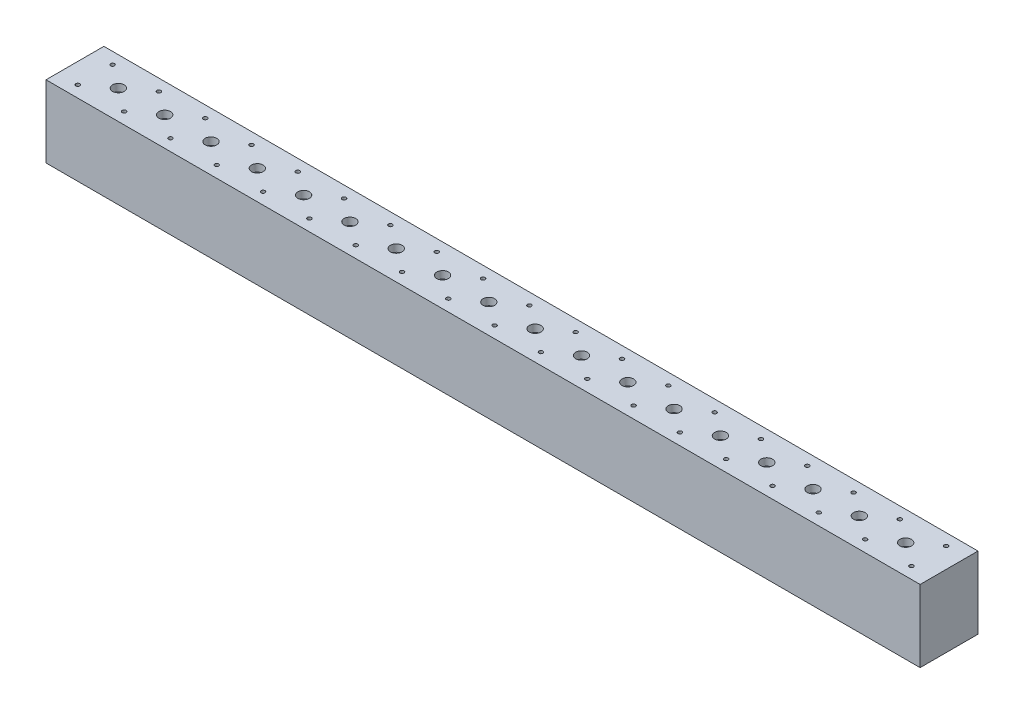
SolidWorks part; units mm, degrees
material "Plain Carbon Steel"
ref_plane "Front Plane" through (0, 0, 0) normal (0, 0, 1) x (1, 0, 0)
ref_plane "Top Plane" through (0, 0, 0) normal (0, 1, 0) x (1, 0, 0)
ref_plane "Right Plane" through (0, 0, 0) normal (1, 0, 0) x (0, 0, -1)
sketch "Sketch1" plane through (0, 0, 0) normal (0, 0, 1) x (1, 0, 0)
  line L0 (-755, 15) -> (755, 15)
  line L3 (755, 15) -> (755, 139.5)
  line L4 (0, 0) -> (0, 15) construction
  line L5 (-755, 15) -> (-755, 139.5)
  line L8 (-755, 139.5) -> (755, 139.5)
  line L9 (755, 15) -> (-755, 15) construction
  dimension "D1" = 124.5
  dimension "D4" = 1510
extrude "Boss-Extrude1" add sketch "Sketch1" against normal blind 100
ref_plane "Plane1" through (0, 0, -50) normal (0, 0, -1) x (-1, 0, 0)
hole_wizard "M8 Tapped Hole1" positions "Sketch4" profile "Sketch3" tap size "M8" standard "ISO"
sketch "Sketch4" plane through (0, 139.5, 0) normal (0, 1, 0) x (1, 0, 0)
  point P0 (720, 80)
  point P3 (720, 20)
  point P6 (640, 20)
  point P9 (640, 80)
  point P12 (560, 80)
  point P15 (560, 20)
  point P18 (480, 20)
  point P21 (480, 80)
  point P24 (400, 80)
  point P27 (400, 20)
  point P30 (320, 20)
  point P33 (320, 80)
  point P36 (240, 80)
  point P39 (240, 20)
  point P42 (160, 20)
  point P45 (160, 80)
  point P48 (80, 80)
  point P51 (80, 20)
  point P54 (0, 20)
  point P57 (0, 80)
  point P60 (-80, 80)
  point P63 (-80, 20)
  point P66 (-160, 20)
  point P69 (-160, 80)
  point P72 (-240, 80)
  point P75 (-240, 20)
  point P78 (-320, 20)
  point P81 (-320, 80)
  point P84 (-400, 80)
  point P87 (-400, 20)
  point P90 (-480, 20)
  point P93 (-480, 80)
  point P96 (-560, 20)
  point P99 (-560, 80)
  point P102 (-640, 20)
  point P105 (-640, 80)
  point P108 (-720, 80)
  point P111 (-720, 20)
sketch "Sketch3" plane through (720, 139.5, -80) normal (1, 0, 0) x (0, 0, 1)
  line L0 (0, 0) -> (0, 24.2929)
  line L1 (0, 24.2929) -> (3.4, 22.25)
  line L2 (3.4, 22.25) -> (3.4, 0)
  line L5 (3.4, 0) -> (0, 0)
  line L10 (0, 24.2929) -> (-3.4, 22.25) construction
  line L11 (0, -6.35) -> (0, 107.95) construction
  dimension "Tap Drill Dia." = 6.8
  dimension "Tap Drill Depth" = 22.25
  dimension "Drill Angle" = 118
cosmetic thread "Hole Thread1" parameters "D1"=16, "D2"=8
cosmetic thread "Hole Thread2" parameters "D1"=16, "D2"=8
cosmetic thread "Hole Thread3" parameters "D1"=16, "D2"=8
cosmetic thread "Hole Thread4" parameters "D1"=16, "D2"=8
cosmetic thread "Hole Thread5" parameters "D1"=16, "D2"=8
cosmetic thread "Hole Thread6" parameters "D1"=16, "D2"=8
cosmetic thread "Hole Thread7" parameters "D1"=16, "D2"=8
cosmetic thread "Hole Thread8" parameters "D1"=16, "D2"=8
cosmetic thread "Hole Thread9" parameters "D1"=16, "D2"=8
cosmetic thread "Hole Thread10" parameters "D1"=16, "D2"=8
cosmetic thread "Hole Thread11" parameters "D1"=16, "D2"=8
cosmetic thread "Hole Thread12" parameters "D1"=16, "D2"=8
cosmetic thread "Hole Thread13" parameters "D1"=16, "D2"=8
cosmetic thread "Hole Thread14" parameters "D1"=16, "D2"=8
cosmetic thread "Hole Thread15" parameters "D1"=16, "D2"=8
cosmetic thread "Hole Thread16" parameters "D1"=16, "D2"=8
cosmetic thread "Hole Thread17" parameters "D1"=16, "D2"=8
cosmetic thread "Hole Thread18" parameters "D1"=16, "D2"=8
cosmetic thread "Hole Thread19" parameters "D1"=16, "D2"=8
cosmetic thread "Hole Thread20" parameters "D1"=16, "D2"=8
cosmetic thread "Hole Thread21" parameters "D1"=16, "D2"=8
cosmetic thread "Hole Thread22" parameters "D1"=16, "D2"=8
cosmetic thread "Hole Thread23" parameters "D1"=16, "D2"=8
cosmetic thread "Hole Thread24" parameters "D1"=16, "D2"=8
cosmetic thread "Hole Thread25" parameters "D1"=16, "D2"=8
cosmetic thread "Hole Thread26" parameters "D1"=16, "D2"=8
cosmetic thread "Hole Thread27" parameters "D1"=16, "D2"=8
cosmetic thread "Hole Thread28" parameters "D1"=16, "D2"=8
cosmetic thread "Hole Thread29" parameters "D1"=16, "D2"=8
cosmetic thread "Hole Thread30" parameters "D1"=16, "D2"=8
cosmetic thread "Hole Thread31" parameters "D1"=16, "D2"=8
cosmetic thread "Hole Thread32" parameters "D1"=16, "D2"=8
cosmetic thread "Hole Thread33" parameters "D1"=16, "D2"=8
cosmetic thread "Hole Thread34" parameters "D1"=16, "D2"=8
cosmetic thread "Hole Thread35" parameters "D1"=16, "D2"=8
cosmetic thread "Hole Thread36" parameters "D1"=16, "D2"=8
cosmetic thread "Hole Thread37" parameters "D1"=16, "D2"=8
cosmetic thread "Hole Thread38" parameters "D1"=16, "D2"=8
sketch "Sketch7" plane through (0, 139.5, 0) normal (0, 1, 0) x (1, 0, 0)
  line L0 (640, 80) -> (720, 80) construction
  line L2 (640, 20) -> (720, 20) construction
  line L4 (680, 80) -> (680, 20) construction
  point P17 (680, 50)
hole_wizard "CBORE for M12 Hex Socket Head Cap Screw1" positions "Sketch7" profile "Sketch6" counterbore size "M12" standard "ISO" end condition through all
sketch "Sketch6" plane through (680, 139.5, -50) normal (1, 0, 0) x (0, 0, 1)
  line L0 (0, 0) -> (0, 124.5)
  line L1 (0, 124.5) -> (6.5, 124.5)
  line L3 (6.5, 124.5) -> (6.5, 12.6)
  line L4 (6.5, 12.6) -> (10, 12.6)
  line L5 (10, 12.6) -> (10, 0)
  line L7 (10, 0) -> (0, 0)
  line L11 (0, -6.35) -> (0, 107.95) construction
  dimension "Thru Hole Dia." = 13
  dimension "Thru Hole Depth" = 124.5
  dimension "C'Bore Dia." = 20
  dimension "C'Bore Depth" = 12.6
pattern_linear "LPattern1" count 18 spacing 80 along (-1, 0, 0) of "CBORE for M12 Hex Socket Head Cap Screw1"
